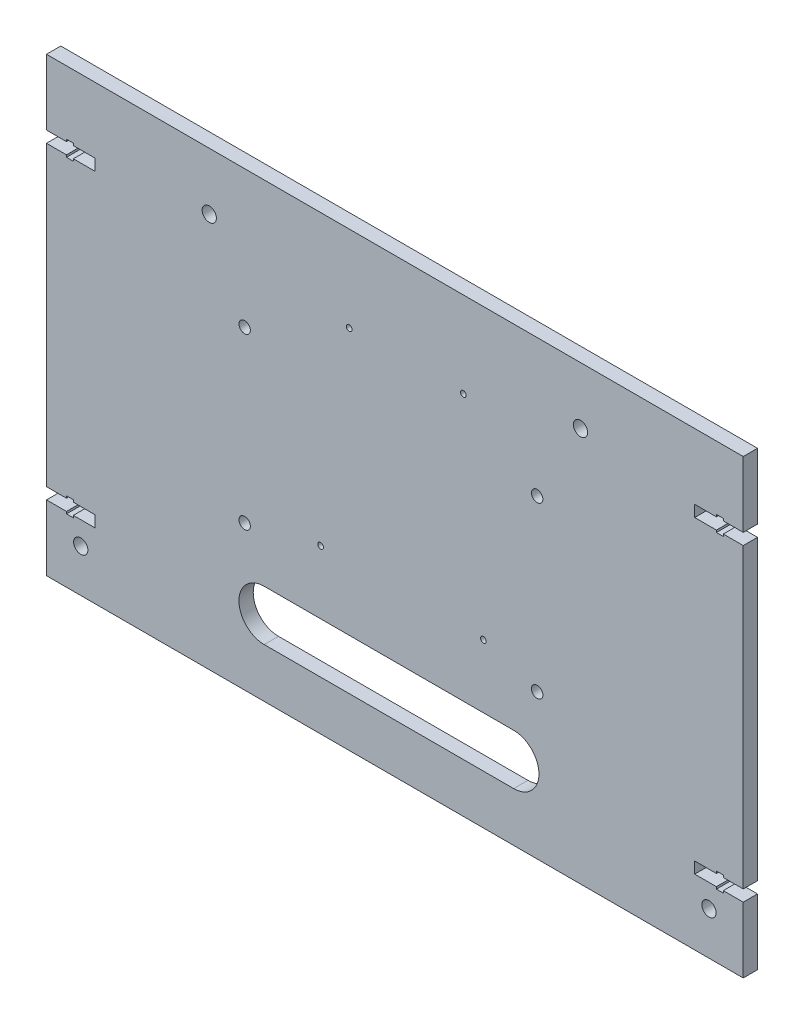
SolidWorks part; units mm, degrees
ref_plane "Front Plane" through (0, 0, 0) normal (0, 0, 1) x (1, 0, 0)
ref_plane "Top Plane" through (0, 0, 0) normal (0, 1, 0) x (1, 0, 0)
ref_plane "Right Plane" through (0, 0, 0) normal (1, 0, 0) x (0, 0, -1)
sketch "Sketch1" plane through (0, 0, 0) normal (0, 0, 1) x (1, 0, 0)
  line L1 (-107.2, 68.15) -> (136.8, 68.15)
  line L2 (-107.2, 68.15) -> (-107.2, -90)
  line L3 (-107.2, -90) -> (136.8, -90)
  line L4 (136.8, 68.15) -> (136.8, -90)
  dimension "D1" = 244
  dimension "D2" = 158.15
extrude "Boss-Extrude1" add sketch "Sketch1" along normal blind 5
sketch "Sketch2" plane through (0, 0, 0) normal (0, 0, -1) x (-1, 0, 0)
  line L0 (-136.8, 45.15) -> (-129.8, 45.15)
  line L1 (-136.8, -90) -> (-136.8, 68.15) construction
  line L2 (-119.8, 45.15) -> (-119.8, 41.15)
  line L3 (-119.8, 41.15) -> (-127.4, 41.15)
  line L4 (-136.8, 41.15) -> (-136.8, 45.15)
  line L5 (-136.8, -10.925) -> (-22.5815, -10.925) construction
  line L6 (-14.8, 68.15) -> (-14.8, -104.887) construction
  line L7 (-136.8, 68.15) -> (107.2, 68.15) construction
  line L8 (-145.5887, 43.15) -> (-78.8198, 43.15) construction
  line L9 (-129.8, 45.15) -> (-129.8, 45.9)
  line L10 (-129.8, 45.9) -> (-127.4, 45.9)
  line L11 (-127.4, 45.9) -> (-127.4, 45.15)
  line L12 (-127.4, 41.15) -> (-127.4, 40.4)
  line L13 (-127.4, 40.4) -> (-129.8, 40.4)
  line L14 (-129.8, 40.4) -> (-129.8, 41.15)
  line L15 (-127.4, 45.15) -> (-119.8, 45.15)
  line L16 (-129.8, 41.15) -> (-136.8, 41.15)
  line L17 (-129.8, -63) -> (-136.8, -63)
  line L18 (-127.4, -67) -> (-119.8, -67)
  line L19 (-129.8, -62.25) -> (-129.8, -63)
  line L20 (-127.4, -62.25) -> (-129.8, -62.25)
  line L21 (-127.4, -63) -> (-127.4, -62.25)
  line L22 (-127.4, -67.75) -> (-127.4, -67)
  line L23 (-129.8, -67.75) -> (-127.4, -67.75)
  line L24 (-129.8, -67) -> (-129.8, -67.75)
  line L25 (-136.8, -63) -> (-136.8, -67)
  line L26 (-119.8, -63) -> (-127.4, -63)
  line L27 (-119.8, -67) -> (-119.8, -63)
  line L28 (-136.8, -67) -> (-129.8, -67)
  line L29 (100.2, 41.15) -> (107.2, 41.15)
  line L30 (97.8, 45.15) -> (90.2, 45.15)
  line L31 (100.2, 40.4) -> (100.2, 41.15)
  line L32 (97.8, 40.4) -> (100.2, 40.4)
  line L33 (97.8, 41.15) -> (97.8, 40.4)
  line L34 (97.8, 45.9) -> (97.8, 45.15)
  line L35 (100.2, 45.9) -> (97.8, 45.9)
  line L36 (100.2, 45.15) -> (100.2, 45.9)
  line L37 (107.2, 41.15) -> (107.2, 45.15)
  line L38 (90.2, 41.15) -> (97.8, 41.15)
  line L39 (90.2, 45.15) -> (90.2, 41.15)
  line L40 (107.2, 45.15) -> (100.2, 45.15)
  line L41 (107.2, -67) -> (100.2, -67)
  line L42 (90.2, -67) -> (90.2, -63)
  line L43 (90.2, -63) -> (97.8, -63)
  line L44 (107.2, -63) -> (107.2, -67)
  line L45 (100.2, -67) -> (100.2, -67.75)
  line L46 (100.2, -67.75) -> (97.8, -67.75)
  line L47 (97.8, -67.75) -> (97.8, -67)
  line L48 (97.8, -63) -> (97.8, -62.25)
  line L49 (97.8, -62.25) -> (100.2, -62.25)
  line L50 (100.2, -62.25) -> (100.2, -63)
  line L51 (97.8, -67) -> (90.2, -67)
  line L52 (100.2, -63) -> (107.2, -63)
  dimension "D1" = 2
  dimension "D2" = 25
  dimension "D3" = 2
  dimension "D4" = 17
  dimension "D5" = 2.4
  dimension "D6" = 0.75
  dimension "D7" = 2.4
  dimension "D8" = 0.75
  dimension "D9" = 7
extrude "Cut-Extrude1" cut sketch "Sketch2" against normal blind 10
sketch "Sketch3" plane through (0, 0, 0) normal (0, 0, -1) x (-1, 0, 0)
  line L0 (-136.8, 68.15) -> (107.2, 68.15) construction
  line L1 (-136.8, -63) -> (-136.8, 41.15) construction
  line L2 (-136.8, -90) -> (-136.8, -67) construction
  line L3 (107.2, -90) -> (-136.8, -90) construction
  circle A1 centre (-124.8, -75.0046) radius 2.5
  circle A3 centre (-79.8, 48.15) radius 2.5
  circle A5 centre (95.2, -75.0046) radius 2.5
  circle A7 centre (50.2, 48.15) radius 2.5
  dimension "D1" = 5
  dimension "D2" = 5
  dimension "D3" = 5
  dimension "D4" = 5
  dimension "D5" = 20
  dimension "D6" = 57
  dimension "D7" = 12
  dimension "D8" = 14.9954
  dimension "D9" = 130
  dimension "D10" = 220
extrude "Cut-Extrude2" cut sketch "Sketch3" against normal blind 10
sketch "Sketch4" plane through (0, 0, 0) normal (0, 0, -1) x (-1, 0, 0)
  line L0 (-136.8, -63) -> (-136.8, 41.15) construction
  line L1 (107.2, -90) -> (-136.8, -90) construction
  line L2 (-136.8, 68.15) -> (107.2, 68.15) construction
  line L3 (-136.8, -10.925) -> (107.2, -10.925) construction
  line L4 (107.2, 41.15) -> (107.2, -63) construction
  line L5 (-14.8, 68.15) -> (-14.8, -90) construction
  circle A1 centre (-38.8, 38.15) radius 1
  circle A3 centre (1.2, 38.15) radius 1
  circle A5 centre (-45.8, -32.925) radius 1
  circle A7 centre (11.2, -32.925) radius 1
  dimension "D1" = 2
  dimension "D2" = 2
  dimension "D3" = 2
  dimension "D4" = 2
  dimension "D5" = 91
  dimension "D6" = 57.075
  dimension "D7" = 57
  dimension "D8" = 98
  dimension "D9" = 30
  dimension "D10" = 40
extrude "Cut-Extrude3" cut sketch "Sketch4" against normal blind 10
sketch "Sketch5" plane through (0, 0, 0) normal (0, 0, -1) x (-1, 0, 0)
  circle A0 centre (-64.6343, 20.0822) radius 2
  circle A1 centre (37.7983, 20.0822) radius 2
  circle A2 centre (37.7983, -39.3002) radius 2
  circle A3 centre (-64.6343, -39.3002) radius 2
  dimension "D1" = 4
  dimension "D2" = 4
  dimension "D3" = 4
  dimension "D4" = 4
extrude "Cut-Extrude4" cut sketch "Sketch5" against normal blind 10
sketch "Sketch6" plane through (0, 0, 0) normal (0, 0, -1) x (-1, 0, 0)
  line L0 (-56.4144, -72.7519) -> (30.96, -72.7519)
  line L2 (30.96, -55.072) -> (-56.4144, -55.072)
  arc A0 (30.96, -55.072) -> (30.96, -72.7519) centre (30.96, -63.912) cw
  arc A1 (-56.4144, -55.072) -> (-56.4144, -72.7519) centre (-56.4144, -63.912) ccw
extrude "Cut-Extrude5" cut sketch "Sketch6" against normal blind 10
